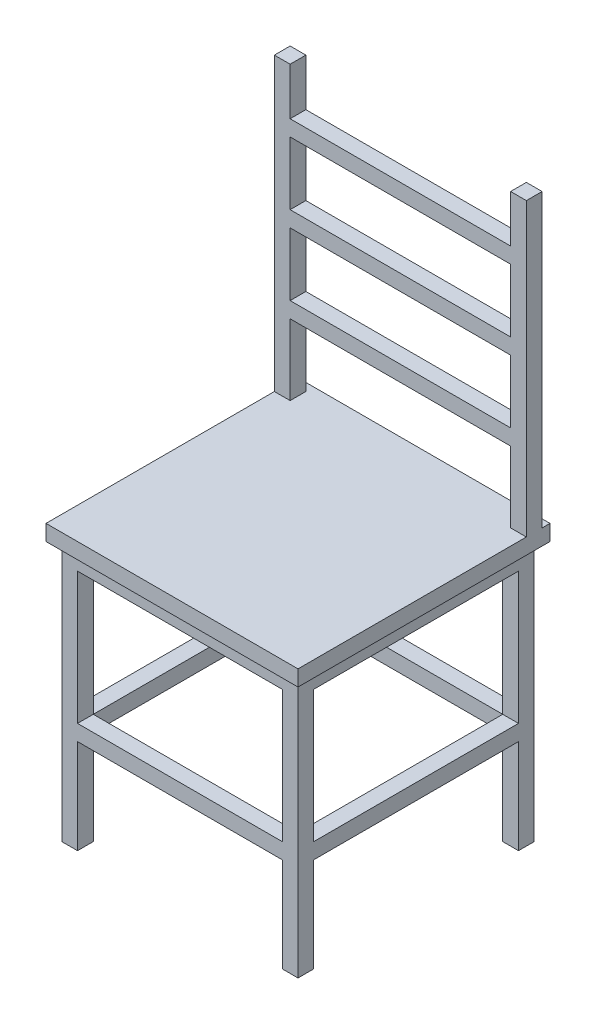
SolidWorks part; units mm, degrees
ref_plane "Front Plane" through (0, 0, 0) normal (0, 0, 1) x (1, 0, 0)
ref_plane "Top Plane" through (0, 0, 0) normal (0, 1, 0) x (1, 0, 0)
ref_plane "Right Plane" through (0, 0, 0) normal (1, 0, 0) x (0, 0, -1)
sketch "Sketch1" plane through (0, 0, 0) normal (0, 1, 0) x (1, 0, 0)
  line L1 (0, 0) -> (406.4, 0)
  line L2 (0, 0) -> (0, 406.4)
  line L3 (0, 406.4) -> (406.4, 406.4)
  line L4 (406.4, 0) -> (406.4, 406.4)
  dimension "D1" = 406.4
  dimension "D2" = 406.4
extrude "Boss-Extrude1" add sketch "Sketch1" along normal blind 25.4
sketch "Sketch2" plane through (0, 0, 0) normal (0, -1, 0) x (1, 0, 0)
  line L0 (406.4, 0) -> (406.4, -406.4) construction
  line L1 (0, 0) -> (406.4, 0)
  line L2 (0, 0) -> (0, -12.7)
  line L3 (0, -12.7) -> (406.4, -12.7)
  line L4 (406.4, 0) -> (406.4, -12.7)
  line L5 (406.4, -406.4) -> (0, -406.4) construction
  line L6 (406.4, 0) -> (393.7, 0)
  line L7 (406.4, 0) -> (406.4, -406.4)
  line L8 (406.4, -406.4) -> (393.7, -406.4)
  line L9 (393.7, 0) -> (393.7, -406.4)
  line L10 (0, -406.4) -> (0, 0) construction
  line L11 (406.4, -406.4) -> (0, -406.4)
  line L12 (406.4, -406.4) -> (406.4, -393.7)
  line L13 (406.4, -393.7) -> (0, -393.7)
  line L14 (0, -406.4) -> (0, -393.7)
  line L16 (0, -406.4) -> (12.7, -406.4)
  line L17 (0, -406.4) -> (0, 0)
  line L18 (0, 0) -> (12.7, 0)
  line L19 (12.7, -406.4) -> (12.7, 0)
  line L20 (12.7, -12.7) -> (393.7, -12.7)
  line L21 (12.7, -12.7) -> (12.7, -38.1)
  line L22 (12.7, -38.1) -> (393.7, -38.1)
  line L23 (393.7, -12.7) -> (393.7, -38.1)
  line L24 (393.7, -12.7) -> (368.3, -12.7)
  line L25 (393.7, -12.7) -> (393.7, -393.7)
  line L26 (393.7, -393.7) -> (368.3, -393.7)
  line L27 (368.3, -12.7) -> (368.3, -393.7)
  line L28 (393.7, -393.7) -> (12.7, -393.7)
  line L29 (393.7, -393.7) -> (393.7, -368.3)
  line L30 (393.7, -368.3) -> (12.7, -368.3)
  line L31 (12.7, -393.7) -> (12.7, -368.3)
  line L32 (12.7, -393.7) -> (38.1, -393.7)
  line L33 (12.7, -393.7) -> (12.7, -12.7)
  line L34 (12.7, -12.7) -> (38.1, -12.7)
  line L35 (38.1, -393.7) -> (38.1, -12.7)
  dimension "D1" = 12.7
  dimension "D2" = 12.7
  dimension "D3" = 12.7
  dimension "D4" = 12.7
  dimension "D5" = 25.4
  dimension "D6" = 25.4
  dimension "D7" = 25.4
  dimension "D8" = 25.4
extrude "Boss-Extrude4" add sketch "Sketch2" along normal blind 28.575 contours L22 L35 L3 L19 | L35 L22 L27 L20 | L30 L35 L22 L19 | L35 L13 L27 L30 | L28 L35 L30 L19 | L25 L30 L27 L13 | L30 L9 L22 L27 | L20 L27 L22 L9
sketch "Sketch4" plane through (0, -28.575, 0) normal (0, -1, 0) x (1, 0, 0)
  line L1 (12.7, -12.7) -> (38.1, -12.7)
  line L2 (12.7, -12.7) -> (12.7, -38.1)
  line L3 (12.7, -38.1) -> (38.1, -38.1)
  line L4 (38.1, -12.7) -> (38.1, -38.1)
  line L5 (368.3, -38.1) -> (393.7, -38.1)
  line L6 (368.3, -38.1) -> (368.3, -12.7)
  line L7 (368.3, -12.7) -> (393.7, -12.7)
  line L8 (393.7, -38.1) -> (393.7, -12.7)
  line L9 (393.7, -393.7) -> (368.3, -393.7)
  line L10 (393.7, -393.7) -> (393.7, -368.3)
  line L11 (393.7, -368.3) -> (368.3, -368.3)
  line L12 (368.3, -393.7) -> (368.3, -368.3)
  line L13 (12.7, -393.7) -> (38.1, -393.7)
  line L14 (12.7, -393.7) -> (12.7, -368.3)
  line L15 (12.7, -368.3) -> (38.1, -368.3)
  line L16 (38.1, -393.7) -> (38.1, -368.3)
extrude "Boss-Extrude5" add sketch "Sketch4" along normal blind 390.525
sketch "Sketch6" plane through (38.1, 0, 0) normal (1, 0, 0) x (0, 0, -1)
  line L0 (12.7, -419.1) -> (12.7, -28.575) construction
  line L1 (12.7, -241.3) -> (38.1, -241.3)
  line L2 (12.7, -241.3) -> (12.7, -266.7)
  line L3 (12.7, -266.7) -> (38.1, -266.7)
  line L4 (38.1, -241.3) -> (38.1, -266.7)
  line L5 (38.1, -419.1) -> (38.1, -28.575) construction
  line L6 (38.1, -419.1) -> (12.7, -419.1) construction
  dimension "D1" = 25.4
  dimension "D2" = 152.4
extrude "Boss-Extrude6" add sketch "Sketch6" along normal blind 355.6
sketch "Sketch8" plane through (0, 0, -38.1) normal (0, 0, -1) x (-1, 0, 0)
  line L0 (-393.7, -419.1) -> (-393.7, -28.575) construction
  line L1 (-368.3, -241.3) -> (-393.7, -241.3)
  line L2 (-368.3, -241.3) -> (-368.3, -266.7)
  line L3 (-368.3, -266.7) -> (-393.7, -266.7)
  line L4 (-393.7, -241.3) -> (-393.7, -266.7)
extrude "Boss-Extrude7" add sketch "Sketch8" along normal blind 355.6
sketch "Sketch9" plane through (368.3, 0, 0) normal (-1, 0, 0) x (0, 0, 1)
  line L0 (-393.7, -419.1) -> (-393.7, -28.575) construction
  line L1 (-368.3, -241.3) -> (-393.7, -241.3)
  line L2 (-368.3, -241.3) -> (-368.3, -266.7)
  line L3 (-368.3, -266.7) -> (-393.7, -266.7)
  line L4 (-393.7, -241.3) -> (-393.7, -266.7)
extrude "Boss-Extrude8" add sketch "Sketch9" along normal blind 355.6
sketch "Sketch10" plane through (0, 0, -368.3) normal (0, 0, 1) x (1, 0, 0)
  line L0 (12.7, -419.1) -> (12.7, -28.575) construction
  line L1 (38.1, -241.3) -> (12.7, -241.3)
  line L2 (38.1, -241.3) -> (38.1, -266.7)
  line L3 (38.1, -266.7) -> (12.7, -266.7)
  line L4 (12.7, -241.3) -> (12.7, -266.7)
extrude "Boss-Extrude9" add sketch "Sketch10" along normal blind 355.6
sketch "Sketch11" plane through (0, 25.4, 0) normal (0, 1, 0) x (1, 0, 0)
  line L0 (406.4, 0) -> (406.4, 406.4) construction
  line L9 (0, 406.4) -> (406.4, 406.4)
  line L10 (0, 406.4) -> (0, 393.7)
  line L11 (0, 393.7) -> (406.4, 393.7)
  line L12 (406.4, 406.4) -> (406.4, 393.7)
  line L14 (0, 393.7) -> (25.4, 393.7)
  line L15 (0, 393.7) -> (0, 368.3)
  line L16 (0, 368.3) -> (25.4, 368.3)
  line L17 (25.4, 393.7) -> (25.4, 368.3)
  line L18 (406.4, 393.7) -> (381, 393.7)
  line L19 (406.4, 393.7) -> (406.4, 368.3)
  line L20 (406.4, 368.3) -> (381, 368.3)
  line L21 (381, 393.7) -> (381, 368.3)
  line M5 (0, 406.4) -> (0, 0)
  line M7 (406.4, 0) -> (406.4, 406.4)
  dimension "D1" = 12.7
  dimension "D2" = 25.4
  dimension "D3" = 25.4
  dimension "D4" = 25.4
  dimension "D5" = 25.4
extrude "Boss-Extrude11" add sketch "Sketch11" along normal blind 469.9 contours L17 L11 L16 M5 | L11 L21 L20 M7
sketch "Sketch12" plane through (381, 0, 0) normal (-1, 0, 0) x (0, 0, 1)
  line L0 (-393.7, 495.3) -> (-393.7, 25.4) construction
  line L1 (-393.7, 419.1) -> (-368.3, 419.1)
  line L2 (-393.7, 419.1) -> (-393.7, 393.7)
  line L3 (-393.7, 393.7) -> (-368.3, 393.7)
  line L4 (-368.3, 419.1) -> (-368.3, 393.7)
  line L5 (-368.3, 495.3) -> (-368.3, 25.4) construction
  line L6 (-393.7, 25.4) -> (-368.3, 25.4) construction
  line L7 (-393.7, 292.1) -> (-368.3, 292.1)
  line L8 (-393.7, 292.1) -> (-393.7, 266.7)
  line L9 (-393.7, 266.7) -> (-368.3, 266.7)
  line L10 (-368.3, 292.1) -> (-368.3, 266.7)
  line L11 (-393.7, 165.1) -> (-368.3, 165.1)
  line L12 (-393.7, 165.1) -> (-393.7, 139.7)
  line L13 (-393.7, 139.7) -> (-368.3, 139.7)
  line L14 (-368.3, 165.1) -> (-368.3, 139.7)
  dimension "D1" = 25.4
  dimension "D2" = 25.4
  dimension "D3" = 25.4
  dimension "D4" = 101.6
  dimension "D5" = 101.6
  dimension "D6" = 114.3
extrude "Boss-Extrude12" add sketch "Sketch12" along normal blind 376.174
